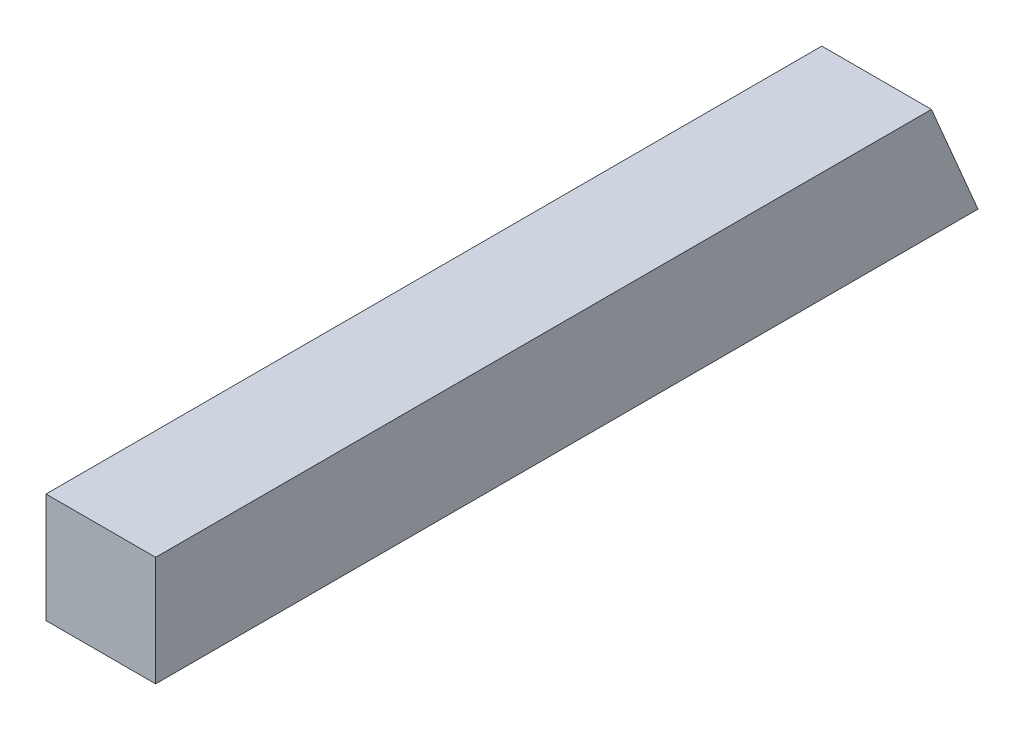
SolidWorks part; units mm, degrees
ref_plane "Front Plane" through (0, 0, 0) normal (0, 0, 1) x (1, 0, 0)
ref_plane "Top Plane" through (0, 0, 0) normal (0, 1, 0) x (1, 0, 0)
ref_plane "Right Plane" through (0, 0, 0) normal (1, 0, 0) x (0, 0, -1)
sketch "Sketch1" plane through (0, 0, 0) normal (0, 0, 1) x (1, 0, 0)
  line L1 (-10, 10) -> (10, 10)
  line L2 (-10, 10) -> (-10, -10)
  line L3 (-10, -10) -> (10, -10)
  line L4 (10, 10) -> (10, -10)
  line L5 (-10, 10) -> (10, -10) construction
  line L6 (-10, -10) -> (10, 10) construction
  point P0 (0, 0)
  dimension "D1" = 20
  dimension "D2" = 20
extrude "Boss-Extrude1" add sketch "Sketch1" along normal blind 150
sketch "Sketch2" plane through (10, 0, 0) normal (1, 0, 0) x (0, 0, -1)
  line L0 (0, -10) -> (-8.4895, 10)
  line L1 (-150, 10) -> (0, 10) construction
  line L2 (-8.4895, 10) -> (0, 10)
  line L3 (0, 10) -> (0, -10)
  dimension "D1" = 23
extrude "Cut-Extrude1" cut sketch "Sketch2" against normal through all
